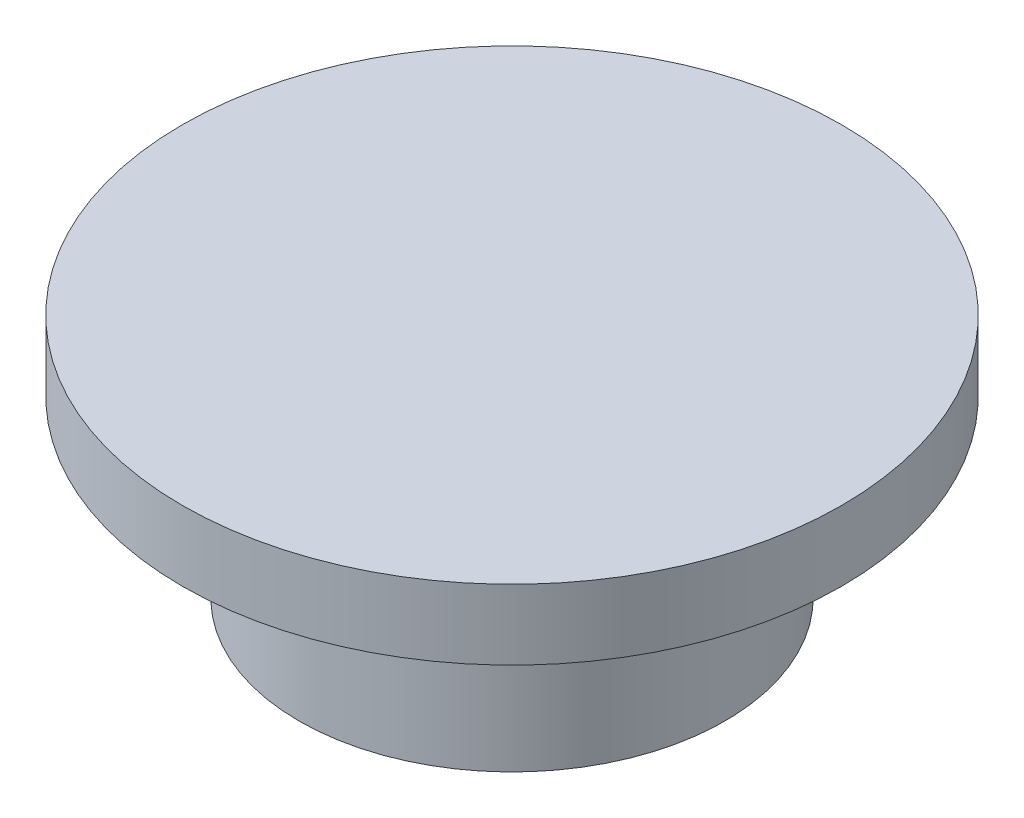
SolidWorks part; units mm, degrees
ref_plane "Спереди" through (0, 0, 0) normal (0, 0, 1) x (1, 0, 0)
ref_plane "Сверху" through (0, 0, 0) normal (0, 1, 0) x (1, 0, 0)
ref_plane "Справа" through (0, 0, 0) normal (1, 0, 0) x (0, 0, -1)
sketch "Эскиз1" plane through (0, 0, 0) normal (0, 0, 1) x (1, 0, 0)
  line L6 (5.3, 0) -> (5.3, 8.4)
  line L7 (5.3, 8.4) -> (11.3, 8.4)
  line L8 (11.3, 8.4) -> (11.3, 6)
  line L9 (11.3, 6) -> (7.3, 6)
  line L10 (7.3, 6) -> (7.3, 0)
  line L11 (7.3, 0) -> (5.3, 0)
  line L12 (0, 0) -> (0, 18.616) construction
  dimension "D1" = 5.3
  dimension "D2" = 2
  dimension "D3" = 2.4
  dimension "D4" = 6
  dimension "D5" = 4
revolve "Повернуть1" add sketch "Эскиз1" angle 360 about L12
sketch "Эскиз2" plane through (0, 8.4, 0) normal (0, 1, 0) x (1, 0, 0)
  circle A0 centre (0, 0) radius 5.5896
extrude "Бобышка-Вытянуть1" add sketch "Эскиз2" against normal blind 0.4
